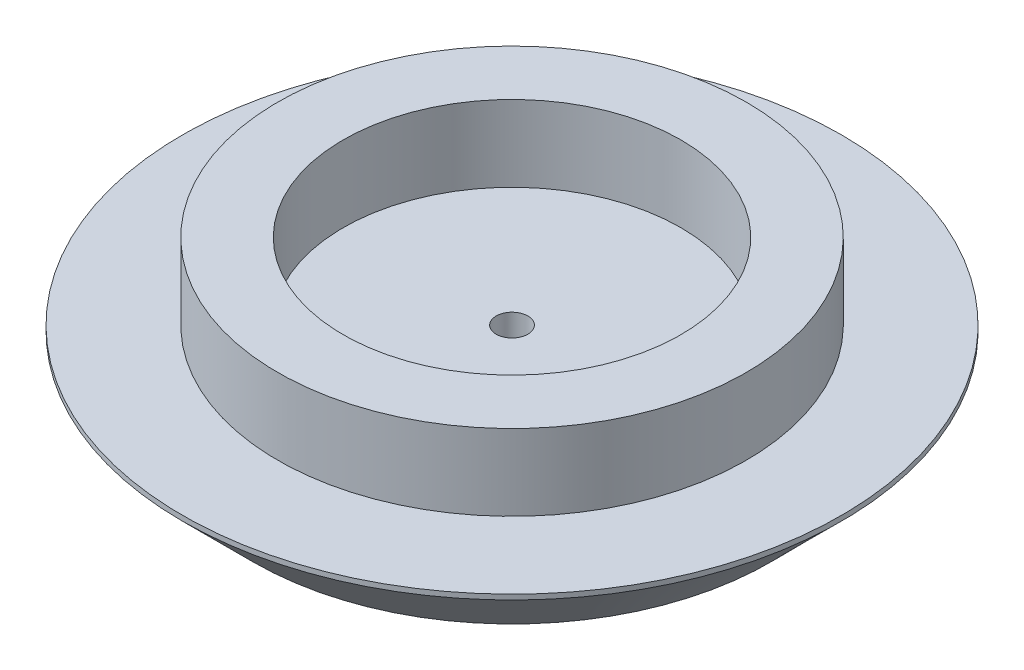
SolidWorks part; units mm, degrees
ref_plane "Front Plane" through (0, 0, 0) normal (0, 0, 1) x (1, 0, 0)
ref_plane "Top Plane" through (0, 0, 0) normal (0, 1, 0) x (1, 0, 0)
ref_plane "Right Plane" through (0, 0, 0) normal (1, 0, 0) x (0, 0, -1)
sketch "Sketch1" plane through (0, 0, 0) normal (0, 0, 1) x (1, 0, 0)
  line L0 (-29.337, 0) -> (-41.275, 0)
  line L1 (-29.337, 0) -> (-29.337, 9.525)
  line L2 (-29.337, 9.525) -> (-21.1455, 9.525)
  line L3 (-21.1455, 9.525) -> (-21.1455, 0)
  line L4 (-21.1455, 0) -> (0, 0)
  line L5 (-41.275, 0) -> (-41.275, -9.525)
  line L6 (-41.275, -9.525) -> (0, -9.525)
  line L7 (0, -9.525) -> (0, 0)
  dimension "D1" = 9.525
  dimension "D2" = 9.525
  dimension "D3" = 21.1455
  dimension "D4" = 29.337
  dimension "D5" = 41.275
revolve "Revolve1" add sketch "Sketch1" angle 360 about L7
chamfer "Chamfer1" distance 8.89 angle 45 1 edges at (0, -9.525, -41.275)
sketch "Sketch9" plane through (0, -9.525, 0) normal (0, -1, 0) x (1, 0, 0)
  line L0 (0, 0) -> (0, 32.385) construction
  circle A0 centre (0, 0) radius 32.385 construction
hole_wizard "5/32 (0.15625) Diameter Hole1" positions "3DSketch5" profile "Sketch11" hole size "5/32" standard "Ansi Inch" end condition up to next
sketch3d "3DSketch5"
  point P0 (0, -9.525, 0)
sketch "Sketch11" plane through (0, -9.525, 0) normal (1, 0, 0) x (0, 0, -1)
  line L0 (0, 0) -> (0, 9.525)
  line L1 (0, 9.525) -> (1.9844, 9.525)
  line L2 (1.9844, 9.525) -> (1.9844, 0)
  line L5 (1.9844, 0) -> (0, 0)
  line L11 (0, -6.35) -> (0, 107.95) construction
  dimension "Thru Hole Dia." = 3.9688
  dimension "Thru Hole Depth" = 9.525
